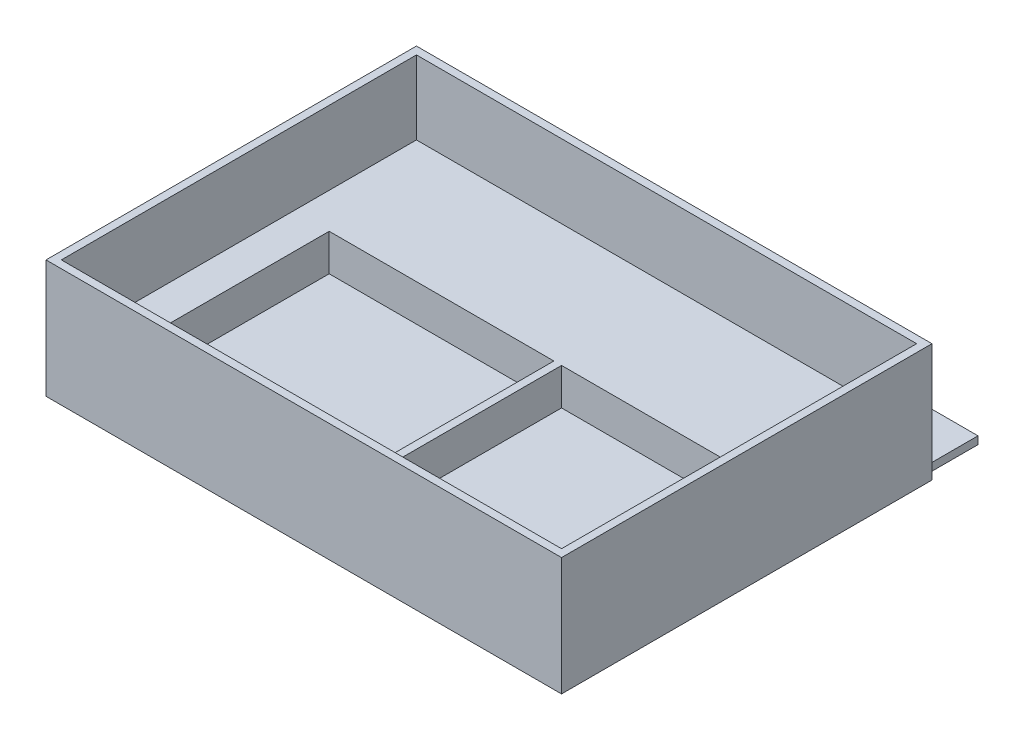
SolidWorks part; units mm, degrees
ref_plane "Front Plane" through (0, 0, 0) normal (0, 0, 1) x (1, 0, 0)
ref_plane "Top Plane" through (0, 0, 0) normal (0, 1, 0) x (1, 0, 0)
ref_plane "Right Plane" through (0, 0, 0) normal (1, 0, 0) x (0, 0, -1)
sketch "Sketch1" plane through (0, 0, 0) normal (0, 1, 0) x (1, 0, 0)
  line L0 (-193.9375, 76.2) -> (-190.7625, 76.2) construction
  line L1 (-304.8, -152.4) -> (304.8, -152.4)
  line L2 (-304.8, -152.4) -> (-304.8, 152.4)
  line L3 (-304.8, 152.4) -> (304.8, 152.4)
  line L4 (304.8, -152.4) -> (304.8, 152.4)
  line L5 (-1.5875, -16.8) -> (-94.5875, -16.8)
  line L6 (-1.5875, -16.8) -> (-1.5875, 76.2)
  line L7 (-97.7625, 76.2) -> (-190.7625, 76.2)
  line L8 (-97.7625, 76.2) -> (-97.7625, -16.8)
  line L9 (-97.7625, -16.8) -> (-190.7625, -16.8)
  line L10 (-190.7625, 76.2) -> (-190.7625, -16.8)
  line L11 (-97.7625, 76.2) -> (-190.7625, -16.8) construction
  line L12 (-97.7625, -16.8) -> (-190.7625, 76.2) construction
  line L13 (-1.5875, 76.2) -> (-94.5875, 76.2)
  line L14 (-94.5875, -16.8) -> (-94.5875, 76.2)
  line L15 (-1.5875, -16.8) -> (-94.5875, 76.2) construction
  line L16 (-1.5875, 76.2) -> (-94.5875, -16.8) construction
  line L17 (-190.7625, -19.975) -> (-97.7625, -19.975)
  line L18 (-190.7625, -19.975) -> (-190.7625, -112.975)
  line L19 (-190.7625, -112.975) -> (-97.7625, -112.975)
  line L20 (-97.7625, -19.975) -> (-97.7625, -112.975)
  line L21 (-190.7625, -19.975) -> (-97.7625, -112.975) construction
  line L22 (-190.7625, -112.975) -> (-97.7625, -19.975) construction
  line L23 (-94.5875, -19.975) -> (-1.5875, -19.975)
  line L24 (-94.5875, -19.975) -> (-94.5875, -112.975)
  line L25 (-94.5875, -112.975) -> (-1.5875, -112.975)
  line L26 (-1.5875, -19.975) -> (-1.5875, -112.975)
  line L27 (-94.5875, -19.975) -> (-1.5875, -112.975) construction
  line L28 (-94.5875, -112.975) -> (-1.5875, -19.975) construction
  line L29 (-286.9375, 76.2) -> (-193.9375, 76.2)
  line L30 (-286.9375, 76.2) -> (-286.9375, -16.8)
  line L31 (-286.9375, -16.8) -> (-193.9375, -16.8)
  line L32 (-193.9375, 76.2) -> (-193.9375, -16.8)
  line L33 (-286.9375, -19.975) -> (-193.9375, -19.975)
  line L34 (-286.9375, -19.975) -> (-286.9375, -112.975)
  line L35 (-286.9375, -112.975) -> (-193.9375, -112.975)
  line L36 (-193.9375, -19.975) -> (-193.9375, -112.975)
  line L37 (1.5875, 76.2) -> (94.5875, 76.2)
  line L38 (1.5875, 76.2) -> (1.5875, -16.8)
  line L39 (1.5875, -16.8) -> (94.5875, -16.8)
  line L40 (94.5875, 76.2) -> (94.5875, -16.8)
  line L41 (1.5875, -19.975) -> (94.5875, -19.975)
  line L42 (1.5875, -19.975) -> (1.5875, -112.975)
  line L43 (1.5875, -112.975) -> (94.5875, -112.975)
  line L44 (94.5875, -19.975) -> (94.5875, -112.975)
  line L45 (-97.7625, 76.2) -> (-94.5875, 76.2) construction
  line L46 (-1.5875, 76.2) -> (1.5875, 76.2) construction
  line L47 (94.5875, 76.2) -> (97.7625, 76.2) construction
  line L48 (97.7625, 76.2) -> (190.7625, 76.2)
  line L49 (97.7625, 76.2) -> (97.7625, -16.8)
  line L50 (97.7625, -16.8) -> (190.7625, -16.8)
  line L51 (190.7625, 76.2) -> (190.7625, -16.8)
  line L52 (97.7625, -19.975) -> (190.7625, -19.975)
  line L53 (97.7625, -19.975) -> (97.7625, -112.975)
  line L54 (97.7625, -112.975) -> (190.7625, -112.975)
  line L55 (190.7625, -19.975) -> (190.7625, -112.975)
  line L56 (1.5875, -16.8) -> (1.5875, -19.975) construction
  line L57 (190.7625, -16.8) -> (193.9375, -16.8) construction
  line L58 (193.9375, 76.2) -> (286.9375, 76.2)
  line L59 (193.9375, 76.2) -> (193.9375, -16.8)
  line L60 (193.9375, -16.8) -> (286.9375, -16.8)
  line L61 (286.9375, 76.2) -> (286.9375, -16.8)
  line L62 (193.9375, -19.975) -> (286.9375, -19.975)
  line L63 (193.9375, -19.975) -> (193.9375, -112.975)
  line L64 (193.9375, -112.975) -> (286.9375, -112.975)
  line L65 (286.9375, -19.975) -> (286.9375, -112.975)
  point P0 (0, 0)
  point P6 (-144.2625, 29.7)
  point P11 (-48.0875, 29.7)
  point P14 (0, 152.4)
  point P16 (-304.8, 0)
  point P18 (-144.2625, -66.475)
  point P23 (-48.0875, -66.475)
  point P60 (0, 76.2)
  dimension "D1" = 93
  dimension "D2" = 304.8
  dimension "D3" = 3.175
  dimension "D4" = 3.175
  dimension "D5" = 609.6
  dimension "D6" = 76.2
extrude "Boss-Extrude1" add sketch "Sketch1" along normal blind 15.24
sketch "Sketch2" plane through (0, 0, 0) normal (0, -1, 0) x (-1, 0, 0)
  line L1 (304.8, -152.4) -> (-304.8, -152.4)
  line L2 (304.8, -152.4) -> (304.8, 152.4)
  line L3 (304.8, 152.4) -> (-304.8, 152.4)
  line L4 (-304.8, -152.4) -> (-304.8, 152.4)
extrude "Boss-Extrude2" add sketch "Sketch2" along normal blind 3.175
sketch "Sketch3" plane through (0, 15.24, 0) normal (0, 1, 0) x (1, 0, 0)
  line L1 (-304.8, -152.4) -> (304.8, -152.4)
  line L2 (-304.8, -152.4) -> (-304.8, 152.4)
  line L3 (-304.8, 152.4) -> (304.8, 152.4)
  line L4 (304.8, -152.4) -> (304.8, 152.4)
  line L5 (-301.625, -127) -> (301.625, -127)
  line L6 (-301.625, -127) -> (-301.625, 127)
  line L7 (-301.625, 127) -> (301.625, 127)
  line L8 (301.625, -127) -> (301.625, 127)
  point P10 (-301.625, 0)
  point P11 (0, 127)
  dimension "D1" = 254
  dimension "D2" = 3.175
extrude "Boss-Extrude3" add sketch "Sketch3" along normal blind 30.48
sketch "Sketch4" plane through (0, 45.72, 0) normal (0, 1, 0) x (1, 0, 0)
  line L0 (301.625, 127) -> (-301.625, 127) construction
  line L1 (-304.8, 130.175) -> (304.8, 130.175)
  line L2 (-304.8, 130.175) -> (-304.8, -130.175)
  line L3 (-304.8, -130.175) -> (304.8, -130.175)
  line L4 (304.8, 130.175) -> (304.8, -130.175)
  line L5 (-301.625, 127) -> (-301.625, -127) construction
  line L6 (301.625, -127) -> (301.625, 127) construction
  line L7 (-301.625, -127) -> (301.625, -127) construction
  dimension "D1" = 3.175
  dimension "D2" = 3.175
  dimension "D3" = 3.175
  dimension "D4" = 3.175
extrude "Cut-Extrude1" cut sketch "Sketch4" against normal offset from surface (45.72 mm away) 3.175 flip side to cut up to face at (0, -3.175, 0)
sketch "Sketch5" plane through (0, 0, 0) normal (0, 1, 0) x (1, 0, 0)
  line L0 (304.8, -152.4) -> (-304.8, -152.4) construction
  line L1 (-304.8, -152.4) -> (-304.8, -130.175) construction
  circle A0 centre (-292.1, -139.7) radius 3.4925
  circle A1 centre (-266.7, -139.7) radius 3.4925
  circle A2 centre (-241.3, -139.7) radius 3.4925
  circle A3 centre (-215.9, -139.7) radius 3.4925
  circle A4 centre (-190.5, -139.7) radius 3.4925
  circle A5 centre (-165.1, -139.7) radius 3.4925
  circle A6 centre (-139.7, -139.7) radius 3.4925
  circle A7 centre (-114.3, -139.7) radius 3.4925
  circle A8 centre (-88.9, -139.7) radius 3.4925
  circle A9 centre (-63.5, -139.7) radius 3.4925
  circle A10 centre (-38.1, -139.7) radius 3.4925
  circle A11 centre (-12.7, -139.7) radius 3.4925
  circle A12 centre (12.7, 139.7) radius 3.4925
  circle A13 centre (38.1, 139.7) radius 3.4925
  circle A14 centre (63.5, 139.7) radius 3.4925
  circle A15 centre (88.9, 139.7) radius 3.4925
  circle A16 centre (114.3, 139.7) radius 3.4925
  circle A17 centre (139.7, 139.7) radius 3.4925
  circle A18 centre (165.1, 139.7) radius 3.4925
  circle A19 centre (190.5, 139.7) radius 3.4925
  circle A20 centre (215.9, 139.7) radius 3.4925
  circle A21 centre (241.3, 139.7) radius 3.4925
  circle A22 centre (-292.1, 139.7) radius 3.4925
  circle A23 centre (-266.7, 139.7) radius 3.4925
  circle A24 centre (-241.3, 139.7) radius 3.4925
  circle A25 centre (-215.9, 139.7) radius 3.4925
  circle A26 centre (-190.5, 139.7) radius 3.4925
  circle A27 centre (-165.1, 139.7) radius 3.4925
  circle A28 centre (-139.7, 139.7) radius 3.4925
  circle A29 centre (-114.3, 139.7) radius 3.4925
  circle A30 centre (-88.9, 139.7) radius 3.4925
  circle A31 centre (-63.5, 139.7) radius 3.4925
  circle A32 centre (-38.1, 139.7) radius 3.4925
  circle A33 centre (-12.7, 139.7) radius 3.4925
  circle A34 centre (266.7, 139.7) radius 3.4925
  circle A35 centre (292.1, 139.7) radius 3.4925
  circle A36 centre (12.7, -139.7) radius 3.4925
  circle A37 centre (38.1, -139.7) radius 3.4925
  circle A38 centre (63.5, -139.7) radius 3.4925
  circle A39 centre (88.9, -139.7) radius 3.4925
  circle A40 centre (114.3, -139.7) radius 3.4925
  circle A41 centre (139.7, -139.7) radius 3.4925
  circle A42 centre (165.1, -139.7) radius 3.4925
  circle A43 centre (190.5, -139.7) radius 3.4925
  circle A44 centre (215.9, -139.7) radius 3.4925
  circle A45 centre (241.3, -139.7) radius 3.4925
  circle A46 centre (266.7, -139.7) radius 3.4925
  circle A47 centre (292.1, -139.7) radius 3.4925
  circle A53 centre (-292.1, -114.3) radius 3.4925 [skipped]
  circle A54 centre (-292.1, -88.9) radius 3.4925 [skipped]
  circle A55 centre (-292.1, -63.5) radius 3.4925 [skipped]
  circle A56 centre (-292.1, -38.1) radius 3.4925 [skipped]
  circle A57 centre (-292.1, -12.7) radius 3.4925 [skipped]
  circle A58 centre (-292.1, 12.7) radius 3.4925 [skipped]
  circle A59 centre (-292.1, 38.1) radius 3.4925 [skipped]
  circle A60 centre (-292.1, 63.5) radius 3.4925 [skipped]
  circle A61 centre (-292.1, 88.9) radius 3.4925 [skipped]
  circle A62 centre (-292.1, 114.3) radius 3.4925 [skipped]
  dimension "D1" = 6.985
  dimension "D2" = 12.7
  dimension "D3" = 12.7
  dimension "D4" = 24
  dimension "D5" = 12
  dimension "D6" = 24
extrude "Cut-Extrude2" cut sketch "Sketch5" against normal through all
sketch "Sketch6" plane through (-94.5875, 0, 0) normal (1, 0, 0) x (0, 0, -1)
  line L1 (155.7418, -83.1354) -> (-171.399, -83.1354)
  line L2 (155.7418, -83.1354) -> (155.7418, 172.9564)
  line L3 (155.7418, 172.9564) -> (-171.399, 172.9564)
  line L4 (-171.399, -83.1354) -> (-171.399, 172.9564)
extrude "Temporary_Cut" cut sketch "Sketch6" along normal through all
sketch "Sketch7" plane through (-94.5875, 0, 0) normal (1, 0, 0) x (0, 0, -1)
  line L0 (152.4, -3.175) -> (-152.4, -3.175) construction
  line L1 (-130.175, 45.72) -> (130.175, 45.72)
  line L2 (-130.175, 45.72) -> (-130.175, -3.175)
  line L3 (-130.175, -3.175) -> (130.175, -3.175)
  line L4 (130.175, 45.72) -> (130.175, -3.175)
  line L5 (130.175, 45.72) -> (130.175, 0) construction
extrude "Temporary_Side" add sketch "Sketch7" along normal blind 3.175
sketch "Sketch8" plane through (0, 0, 19.975) normal (0, 0, 1) x (1, 0, 0)
  line L1 (-365.6769, 148.6049) -> (15.7213, 148.6049)
  line L2 (-365.6769, 148.6049) -> (-365.6769, -117.0484)
  line L3 (-365.6769, -117.0484) -> (15.7213, -117.0484)
  line L4 (15.7213, 148.6049) -> (15.7213, -117.0484)
extrude "Cut-Extrude3" cut sketch "Sketch8" along normal through all
sketch "Sketch9" plane through (0, 0, 19.975) normal (0, 0, 1) x (1, 0, 0)
  line L1 (-304.8, -3.175) -> (-91.4125, -3.175)
  line L2 (-304.8, -3.175) -> (-304.8, 45.72)
  line L3 (-304.8, 45.72) -> (-91.4125, 45.72)
  line L4 (-91.4125, -3.175) -> (-91.4125, 45.72)
extrude "Boss-Extrude4" add sketch "Sketch9" along normal blind 3.175
